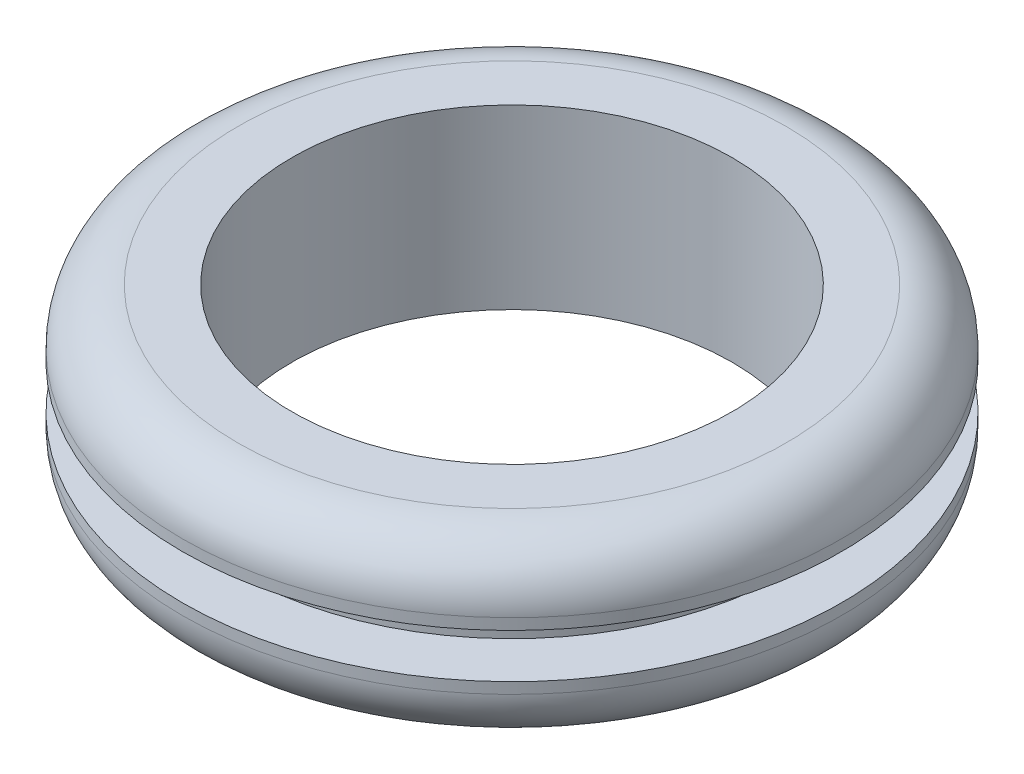
SolidWorks part; units mm, degrees
ref_plane "Plan de face" through (0, 0, 0) normal (0, 0, 1) x (1, 0, 0)
ref_plane "Plan de dessus" through (0, 0, 0) normal (0, 1, 0) x (1, 0, 0)
ref_plane "Plan de droite" through (0, 0, 0) normal (1, 0, 0) x (0, 0, -1)
sketch "Esquisse2" plane through (0, 0, 0) normal (0, 0, 1) x (1, 0, 0)
  line L0 (7.95, 3.2) -> (7.95, 0)
  line L1 (7.95, 0) -> (10, 0)
  line L2 (10, 0) -> (10, 0.8)
  line L3 (10, 0.8) -> (11.9, 0.8)
  line L4 (11.9, 0.8) -> (11.9, 1.2)
  line L5 (9.9, 3.2) -> (7.95, 3.2)
  line L6 (0, 0) -> (0, 60.2514) construction
  arc A0 (11.9, 1.2) -> (9.9, 3.2) centre (9.9, 1.2) ccw
  dimension "D6" = 2
  dimension "D1" = 10
  dimension "D2" = 3.2
  dimension "D3" = 0.8
  dimension "D4" = 11.9
  dimension "D5" = 7.95
revolve "Révolution1" add sketch "Esquisse2" angle 360 about L6
mirror "Symétrie1" about plane through (0, 0, 0) normal (0, 1, 0) of "Révolution1"
